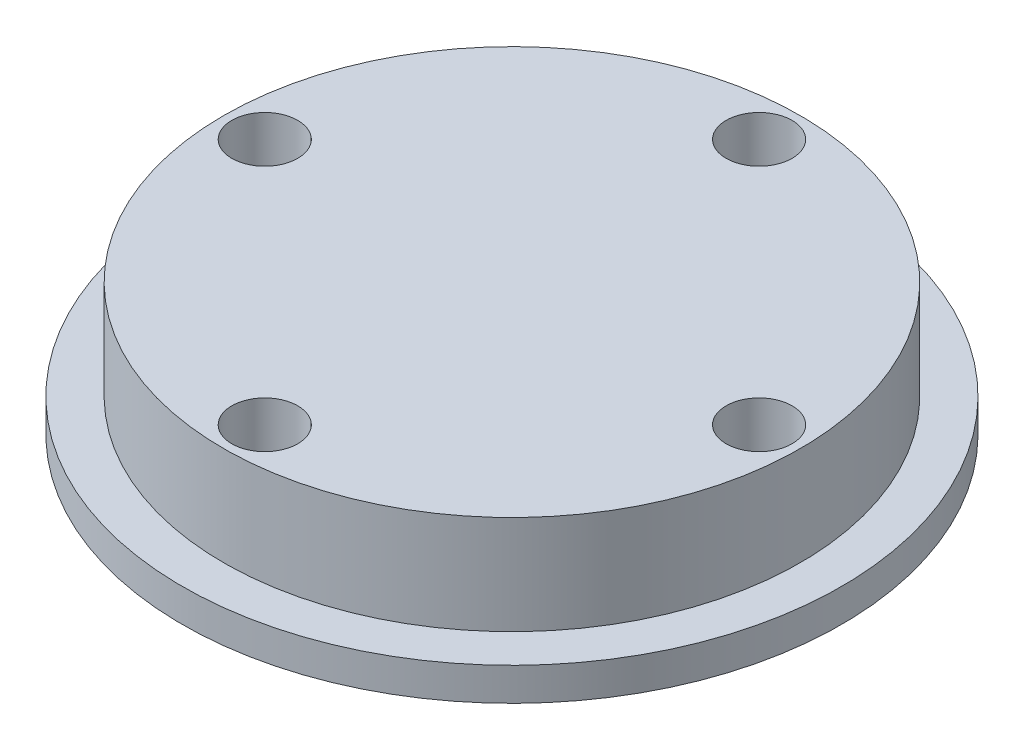
SolidWorks part; units mm, degrees
ref_plane "Front" through (0, 0, 0) normal (0, 0, 1) x (1, 0, 0)
ref_plane "Top" through (0, 0, 0) normal (0, 1, 0) x (1, 0, 0)
ref_plane "Right" through (0, 0, 0) normal (1, 0, 0) x (0, 0, -1)
sketch "草图2" plane through (0, 0, 0) normal (0, 0, 1) x (1, 0, 0)
  line L0 (-44.0615, 0) -> (52.7034, 0) construction
  line L1 (0, 23.2453) -> (0, -12.7367) construction
  line L2 (0, 0) -> (-20, 0)
  line L3 (-20, 0) -> (-20, 2)
  line L4 (-20, 2) -> (-17.5, 2)
  line L5 (-17.5, 2) -> (-17.5, 8)
  line L6 (-17.5, 8) -> (0, 8)
  line L7 (0, 8) -> (0, 0)
  dimension "D1" = 20
  dimension "D2" = 17.5
  dimension "D3" = 2
  dimension "D4" = 6
revolve "旋转1" add sketch "草图2" angle 360 about L7
sketch "草图3" plane through (0, 8, 0) normal (0, 1, 0) x (1, 0, 0)
  circle A0 centre (0, 15) radius 2
  circle A1 centre (15, 0) radius 2
  circle A2 centre (0, -15) radius 2
  circle A3 centre (-15, 0) radius 2
  point P12 (0, 0)
  dimension "D1" = 4
  dimension "D2" = 15
  dimension "D3" = 4
extrude "切除-拉伸1" cut sketch "草图3" against normal up to next and the other way through all
